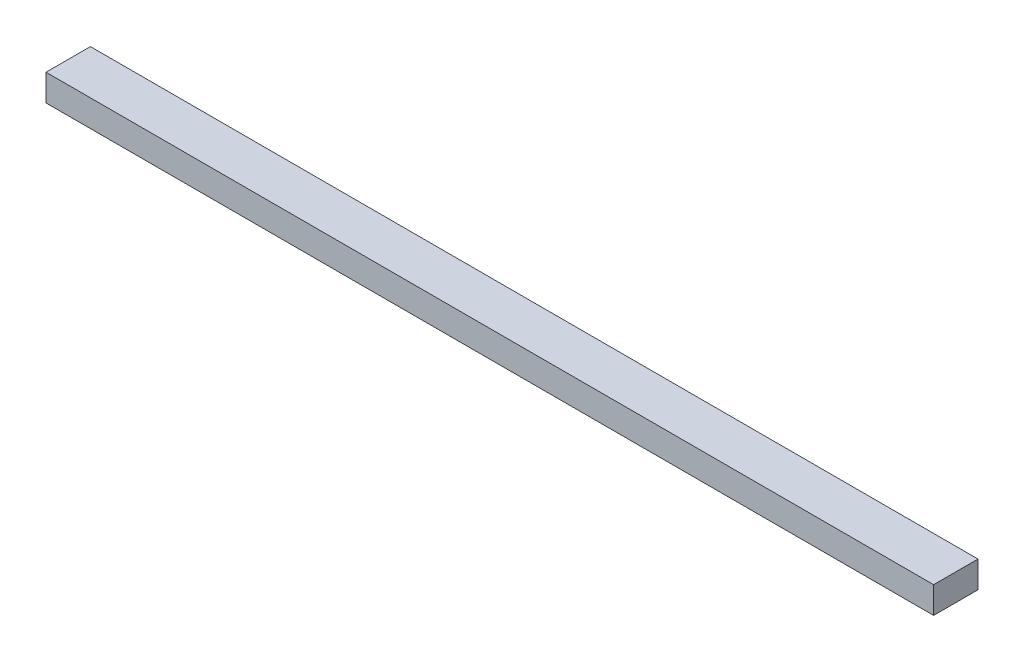
SolidWorks part; units mm, degrees
ref_plane "Front Plane" through (0, 0, 0) normal (0, 0, 1) x (1, 0, 0)
ref_plane "Top Plane" through (0, 0, 0) normal (0, 1, 0) x (1, 0, 0)
ref_plane "Right Plane" through (0, 0, 0) normal (1, 0, 0) x (0, 0, -1)
sketch "Sketch1" plane through (0, 0, 0) normal (0, 1, 0) x (1, 0, 0)
  line L1 (0, 0) -> (100, 0)
  line L2 (0, 0) -> (0, 5)
  line L3 (0, 5) -> (100, 5)
  line L4 (100, 0) -> (100, 5)
  dimension "D1" = 5
  dimension "D2" = 100
extrude "Boss-Extrude1" add sketch "Sketch1" along normal blind 3
